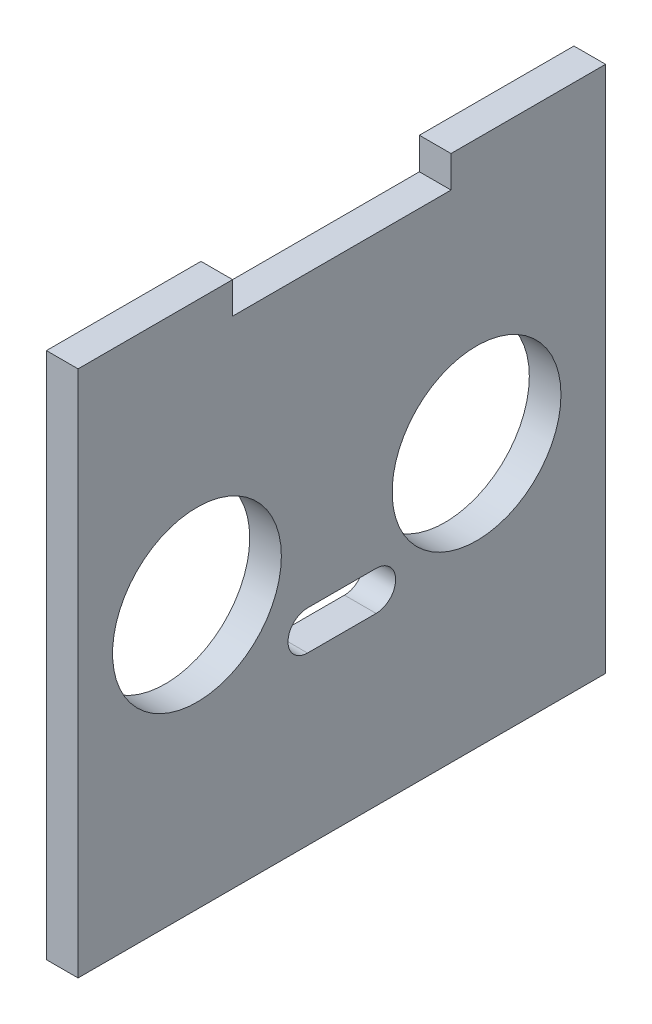
SolidWorks part; units mm, degrees
ref_plane "Front Plane" through (0, 0, 0) normal (0, 0, 1) x (1, 0, 0)
ref_plane "Top Plane" through (0, 0, 0) normal (0, 1, 0) x (1, 0, 0)
ref_plane "Right Plane" through (0, 0, 0) normal (1, 0, 0) x (0, 0, -1)
sketch "Sketch1" plane through (0, 0, 0) normal (1, 0, 0) x (0, 0, -1)
  line L0 (-25, 25) -> (-10.35, 25)
  line L2 (-25, 25) -> (-25, -25)
  line L3 (-25, -25) -> (25, -25)
  line L4 (25, 25) -> (25, -25)
  line L5 (0, -25) -> (0, 25) construction
  line L6 (-25, 0) -> (25, 0) construction
  line L7 (-10.35, 25) -> (-10.35, 22)
  line L8 (-10.35, 22) -> (10.35, 22)
  line L9 (10.35, 22) -> (10.35, 25)
  line L10 (10.35, 25) -> (25, 25)
  point P0 (0, 0)
  point P7 (0, 22)
  dimension "D1" = 20.7
  dimension "D2" = 50
  dimension "D3" = 3
extrude "Boss-Extrude1" add sketch "Sketch1" along normal blind 3
sketch "Sketch2" plane through (3, 0, 0) normal (1, 0, 0) x (0, 0, -1)
  line L0 (-3.25, -7.35) -> (3.25, -7.35) construction
  line L1 (-3.25, -5.5) -> (3.25, -5.5)
  line L2 (-3.25, -9.2) -> (3.25, -9.2)
  circle A0 centre (-13.73, 0) radius 8
  circle A1 centre (12.77, 0) radius 8
  arc A2 (-3.25, -5.5) -> (-3.25, -9.2) centre (-3.25, -7.35) ccw
  arc A3 (3.25, -9.2) -> (3.25, -5.5) centre (3.25, -7.35) ccw
  point P7 (0, -7.35)
  dimension "D1" = 16
  dimension "D6" = 7.35
  dimension "D2" = 26.5
  dimension "D3" = 12.77
  dimension "D4" = 3.7
  dimension "D5" = 6.5
extrude "Cut-Extrude1" cut sketch "Sketch2" against normal through all
